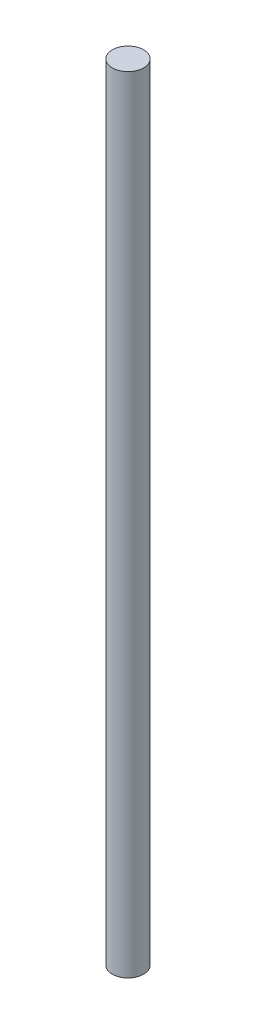
SolidWorks part; units mm, degrees
ref_plane "Front Plane" through (0, 0, 0) normal (0, 0, 1) x (1, 0, 0)
ref_plane "Top Plane" through (0, 0, 0) normal (0, 1, 0) x (1, 0, 0)
ref_plane "Right Plane" through (0, 0, 0) normal (1, 0, 0) x (0, 0, -1)
sketch "Sketch1" plane through (0, 0, 0) normal (0, 1, 0) x (1, 0, 0)
  circle A0 centre (0, 0) radius 6
  dimension "D1" = 12
extrude "Boss-Extrude1" add sketch "Sketch1" along normal mid plane 300
